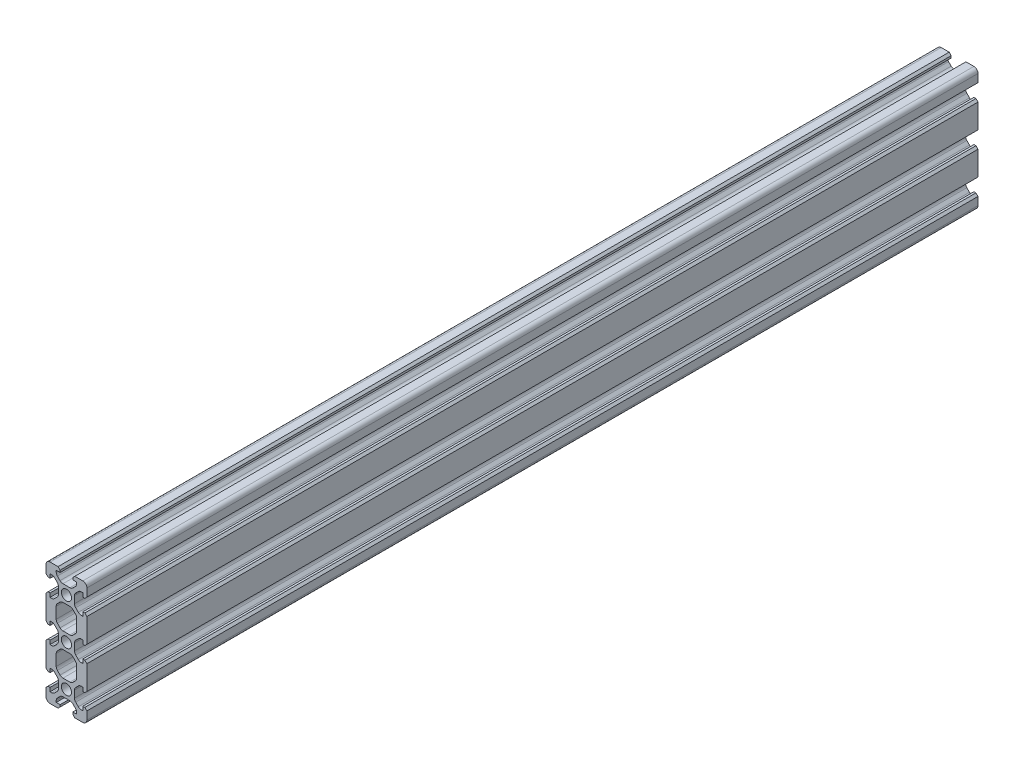
SolidWorks part; units mm, degrees
ref_plane "Front Plane" through (0, 0, 0) normal (0, 0, 1) x (1, 0, 0)
ref_plane "Top Plane" through (0, 0, 0) normal (0, 1, 0) x (1, 0, 0)
ref_plane "Right Plane" through (0, 0, 0) normal (1, 0, 0) x (0, 0, -1)
sketch "Sketch1" plane through (0, 0, 0) normal (0, 0, 1) x (1, 0, 0)
  line B0 (3.1, 29) -> (4.1, 30)
  line B1 (9, -23.1) -> (10, -24.1)
  line B2 (4.4142, -14.1716) -> (3.1236, -15.4621)
  line B3 (10, -15.9) -> (9, -16.9)
  line B4 (5.8284, -24.4142) -> (4.5379, -23.1236)
  line B5 (7.2426, -25) -> (8, -25)
  line B6 (8, -23.1) -> (8, -25)
  line B7 (7.2426, -15) -> (8, -15)
  line B8 (-1.7094, -16.0479) -> (1.7094, -16.0479)
  line B9 (8, -15) -> (8, -16.9)
  line B10 (8, -16.9) -> (9, -16.9)
  line B11 (8, -23.1) -> (9, -23.1)
  line B12 (3.9521, -18.2906) -> (3.9521, -21.7094)
  line B13 (-3.1236, -15.4621) -> (-4.4142, -14.1716)
  line B14 (10, -24.1) -> (10, -28)
  line B15 (4.5379, -16.8764) -> (5.8284, -15.5858)
  line B16 (-3.1, -29) -> (-4.1, -30)
  line B17 (8, -30) -> (4.1, -30)
  line B18 (4.1, -30) -> (3.1, -29)
  line B19 (-4.4142, -25.8284) -> (-3.1236, -24.5379)
  line B20 (-5, -27.2426) -> (-5, -28)
  line B21 (-3.1, -28) -> (-5, -28)
  line B22 (5, -27.2426) -> (5, -28)
  line B23 (5, -28) -> (3.1, -28)
  line B24 (3.1, -28) -> (3.1, -29)
  line B25 (-3.1, -28) -> (-3.1, -29)
  line B26 (1.7094, -23.9521) -> (-1.7094, -23.9521)
  line B27 (-4.1, -30) -> (-8, -30)
  line B28 (3.1236, -24.5379) -> (4.4142, -25.8284)
  line B29 (-9, -16.9) -> (-10, -15.9)
  line B30 (-10, -28) -> (-10, -24.1)
  line B31 (-10, -24.1) -> (-9, -23.1)
  line B32 (-5.8284, -15.5858) -> (-4.5379, -16.8764)
  line B33 (-7.2426, -15) -> (-8, -15)
  line B34 (-8, -16.9) -> (-8, -15)
  line B35 (-7.2426, -25) -> (-8, -25)
  line B36 (-8, -25) -> (-8, -23.1)
  line B37 (-8, -23.1) -> (-9, -23.1)
  line B38 (-8, -16.9) -> (-9, -16.9)
  line B39 (-3.9521, -21.7094) -> (-3.9521, -18.2906)
  line B40 (-4.5379, -23.1236) -> (-5.8284, -24.4142)
  circle B41 centre (0, -20) radius 2.5
  arc B42 (-4.5379, -16.8764) -> (-3.9521, -18.2906) centre (-5.9521, -18.2906) cw
  arc B43 (-5.8284, -15.5858) -> (-7.2426, -15) centre (-7.2426, -17) ccw
  arc B44 (-5, -12.7574) -> (-4.4142, -14.1716) centre (-3, -12.7574) ccw
  arc B45 (5, -12.7574) -> (4.4142, -14.1716) centre (3, -12.7574) cw
  arc B46 (7.2426, -15) -> (5.8284, -15.5858) centre (7.2426, -17) ccw
  arc B47 (5.8284, -24.4142) -> (7.2426, -25) centre (7.2426, -23) ccw
  arc B48 (5, -27.2426) -> (4.4142, -25.8284) centre (3, -27.2426) ccw
  arc B49 (-4.4142, -25.8284) -> (-5, -27.2426) centre (-3, -27.2426) ccw
  arc B50 (-7.2426, -25) -> (-5.8284, -24.4142) centre (-7.2426, -23) ccw
  arc B51 (-3.9521, -21.7094) -> (-4.5379, -23.1236) centre (-5.9521, -21.7094) cw
  arc B52 (-3.1236, -24.5379) -> (-1.7094, -23.9521) centre (-1.7094, -25.9521) cw
  arc B53 (1.7094, -23.9521) -> (3.1236, -24.5379) centre (1.7094, -25.9521) cw
  arc B54 (4.5379, -23.1236) -> (3.9521, -21.7094) centre (5.9521, -21.7094) cw
  arc B55 (3.9521, -18.2906) -> (4.5379, -16.8764) centre (5.9521, -18.2906) cw
  arc B56 (1.7094, -16.0479) -> (3.1236, -15.4621) centre (1.7094, -14.0479) ccw
  arc B57 (-1.7094, -16.0479) -> (-3.1236, -15.4621) centre (-1.7094, -14.0479) cw
  arc B58 (-8, -30) -> (-10, -28) centre (-8, -28) cw
  arc B59 (10, -28) -> (8, -30) centre (8, -28) cw
  line B60 (9, -3.1) -> (10, -4.1)
  line B61 (5, 7.2426) -> (5, 12.7574)
  line B62 (4.4142, 5.8284) -> (3.1236, 4.5379)
  line B63 (8, 5) -> (8, 3.1)
  line B64 (10, 15.9) -> (10, 4.1)
  line B65 (-10, -4.1) -> (-9, -3.1)
  line B66 (7.2426, -5) -> (8, -5)
  line B67 (8, -3.1) -> (9, -3.1)
  line B68 (-8, -3.1) -> (-9, -3.1)
  line B69 (10, 4.1) -> (9, 3.1)
  line B70 (-5, -7.2426) -> (-5, -12.7574)
  line B71 (-10, 4.1) -> (-10, 15.9)
  line B72 (-5, 7.2426) -> (-5, 12.7574)
  line B73 (3.1236, -4.5379) -> (4.4142, -5.8284)
  line B74 (-8, -5) -> (-8, -3.1)
  line B75 (-3.9521, -1.7094) -> (-3.9521, 1.7094)
  line B76 (8, 3.1) -> (9, 3.1)
  line B77 (-8, 3.1) -> (-8, 5)
  line B78 (8, -3.1) -> (8, -5)
  line B79 (1.7094, -3.9521) -> (-1.7094, -3.9521)
  line B80 (7.2426, 5) -> (8, 5)
  line B81 (10, -4.1) -> (10, -15.9)
  line B82 (-9, 3.1) -> (-10, 4.1)
  line B83 (4.5379, 3.1236) -> (5.8284, 4.4142)
  line B84 (-5.8284, 4.4142) -> (-4.5379, 3.1236)
  line B85 (3.9521, 1.7094) -> (3.9521, -1.7094)
  line B86 (-7.2426, 5) -> (-8, 5)
  line B87 (-1.7094, 3.9521) -> (1.7094, 3.9521)
  line B88 (-4.5379, -3.1236) -> (-5.8284, -4.4142)
  line B89 (-10, -15.9) -> (-10, -4.1)
  line B90 (-4.4142, -5.8284) -> (-3.1236, -4.5379)
  line B91 (5.8284, -4.4142) -> (4.5379, -3.1236)
  line B92 (-3.1236, 4.5379) -> (-4.4142, 5.8284)
  line B93 (5, -7.2426) -> (5, -12.7574)
  line B94 (-7.2426, -5) -> (-8, -5)
  line B95 (-8, 3.1) -> (-9, 3.1)
  arc B96 (1.7094, -3.9521) -> (3.1236, -4.5379) centre (1.7094, -5.9521) cw
  arc B97 (3.9521, 1.7094) -> (4.5379, 3.1236) centre (5.9521, 1.7094) cw
  arc B98 (4.5379, -3.1236) -> (3.9521, -1.7094) centre (5.9521, -1.7094) cw
  arc B99 (-4.4142, -5.8284) -> (-5, -7.2426) centre (-3, -7.2426) ccw
  arc B100 (-5, 7.2426) -> (-4.4142, 5.8284) centre (-3, 7.2426) ccw
  arc B101 (1.7094, 3.9521) -> (3.1236, 4.5379) centre (1.7094, 5.9521) ccw
  arc B102 (5, -7.2426) -> (4.4142, -5.8284) centre (3, -7.2426) ccw
  arc B103 (-7.2426, -5) -> (-5.8284, -4.4142) centre (-7.2426, -3) ccw
  arc B104 (5, 7.2426) -> (4.4142, 5.8284) centre (3, 7.2426) cw
  circle B105 centre (0, 0) radius 2.5
  arc B106 (-1.7094, 3.9521) -> (-3.1236, 4.5379) centre (-1.7094, 5.9521) cw
  arc B107 (-3.9521, -1.7094) -> (-4.5379, -3.1236) centre (-5.9521, -1.7094) cw
  arc B108 (-3.1236, -4.5379) -> (-1.7094, -3.9521) centre (-1.7094, -5.9521) cw
  arc B109 (-5.8284, 4.4142) -> (-7.2426, 5) centre (-7.2426, 3) ccw
  arc B110 (5.8284, -4.4142) -> (7.2426, -5) centre (7.2426, -3) ccw
  arc B111 (-4.5379, 3.1236) -> (-3.9521, 1.7094) centre (-5.9521, 1.7094) cw
  arc B112 (7.2426, 5) -> (5.8284, 4.4142) centre (7.2426, 3) ccw
  line B113 (8, 25) -> (8, 23.1)
  line B114 (3.9521, 21.7094) -> (3.9521, 18.2906)
  line B115 (-4.1, 30) -> (-3.1, 29)
  line B116 (-5, 27.2426) -> (-5, 28)
  line B117 (-5.8284, 24.4142) -> (-4.5379, 23.1236)
  line B118 (8, 16.9) -> (9, 16.9)
  line B119 (3.1, 28) -> (3.1, 29)
  line B120 (1.7094, 16.0479) -> (-1.7094, 16.0479)
  line B121 (-8, 16.9) -> (-9, 16.9)
  line B122 (-3.1236, 24.5379) -> (-4.4142, 25.8284)
  line B123 (3.1, 28) -> (5, 28)
  line B124 (-8, 23.1) -> (-8, 25)
  line B125 (8, 16.9) -> (8, 15)
  line B126 (-10, 15.9) -> (-9, 16.9)
  line B127 (-3.1, 28) -> (-3.1, 29)
  line B128 (3.1236, 15.4621) -> (4.4142, 14.1716)
  line B129 (5.8284, 15.5858) -> (4.5379, 16.8764)
  line B130 (10, 28) -> (10, 24.1)
  line B131 (-8, 15) -> (-8, 16.9)
  line B132 (7.2426, 25) -> (8, 25)
  line B133 (-5, 28) -> (-3.1, 28)
  line B134 (5, 27.2426) -> (5, 28)
  line B135 (-7.2426, 15) -> (-8, 15)
  line B136 (9, 16.9) -> (10, 15.9)
  line B137 (-9, 23.1) -> (-10, 24.1)
  line B138 (4.5379, 23.1236) -> (5.8284, 24.4142)
  line B139 (-4.4142, 14.1716) -> (-3.1236, 15.4621)
  line B140 (4.4142, 25.8284) -> (3.1236, 24.5379)
  line B141 (-3.9521, 18.2906) -> (-3.9521, 21.7094)
  line B142 (4.1, 30) -> (8, 30)
  line B143 (-8, 30) -> (-4.1, 30)
  line B144 (10, 24.1) -> (9, 23.1)
  line B145 (-1.7094, 23.9521) -> (1.7094, 23.9521)
  line B146 (7.2426, 15) -> (8, 15)
  line B147 (-10, 24.1) -> (-10, 28)
  line B148 (-7.2426, 25) -> (-8, 25)
  line B149 (-8, 23.1) -> (-9, 23.1)
  line B150 (8, 23.1) -> (9, 23.1)
  line B151 (-4.5379, 16.8764) -> (-5.8284, 15.5858)
  arc B152 (-5, 27.2426) -> (-4.4142, 25.8284) centre (-3, 27.2426) ccw
  arc B153 (-7.2426, 15) -> (-5.8284, 15.5858) centre (-7.2426, 17) ccw
  arc B154 (1.7094, 16.0479) -> (3.1236, 15.4621) centre (1.7094, 14.0479) cw
  arc B155 (-4.4142, 14.1716) -> (-5, 12.7574) centre (-3, 12.7574) ccw
  arc B156 (1.7094, 23.9521) -> (3.1236, 24.5379) centre (1.7094, 25.9521) ccw
  circle B157 centre (0, 20) radius 2.5
  arc B158 (-10, 28) -> (-8, 30) centre (-8, 28) cw
  arc B159 (4.5379, 16.8764) -> (3.9521, 18.2906) centre (5.9521, 18.2906) cw
  arc B160 (-3.1236, 15.4621) -> (-1.7094, 16.0479) centre (-1.7094, 14.0479) cw
  arc B161 (5, 27.2426) -> (4.4142, 25.8284) centre (3, 27.2426) cw
  arc B162 (5, 12.7574) -> (4.4142, 14.1716) centre (3, 12.7574) ccw
  arc B163 (-4.5379, 23.1236) -> (-3.9521, 21.7094) centre (-5.9521, 21.7094) cw
  arc B164 (8, 30) -> (10, 28) centre (8, 28) cw
  arc B165 (-3.9521, 18.2906) -> (-4.5379, 16.8764) centre (-5.9521, 18.2906) cw
  arc B166 (3.9521, 21.7094) -> (4.5379, 23.1236) centre (5.9521, 21.7094) cw
  arc B167 (-5.8284, 24.4142) -> (-7.2426, 25) centre (-7.2426, 23) ccw
  arc B168 (-1.7094, 23.9521) -> (-3.1236, 24.5379) centre (-1.7094, 25.9521) cw
  arc B169 (5.8284, 15.5858) -> (7.2426, 15) centre (7.2426, 17) ccw
  arc B170 (7.2426, 25) -> (5.8284, 24.4142) centre (7.2426, 23) ccw
sketch_block_instance "2060-1"
sketch_block "2060" parameters "D1"=2, "D2"=2, "D3"=2
extrude "Boss-Extrude1" add sketch "Sketch1" along normal blind 436
